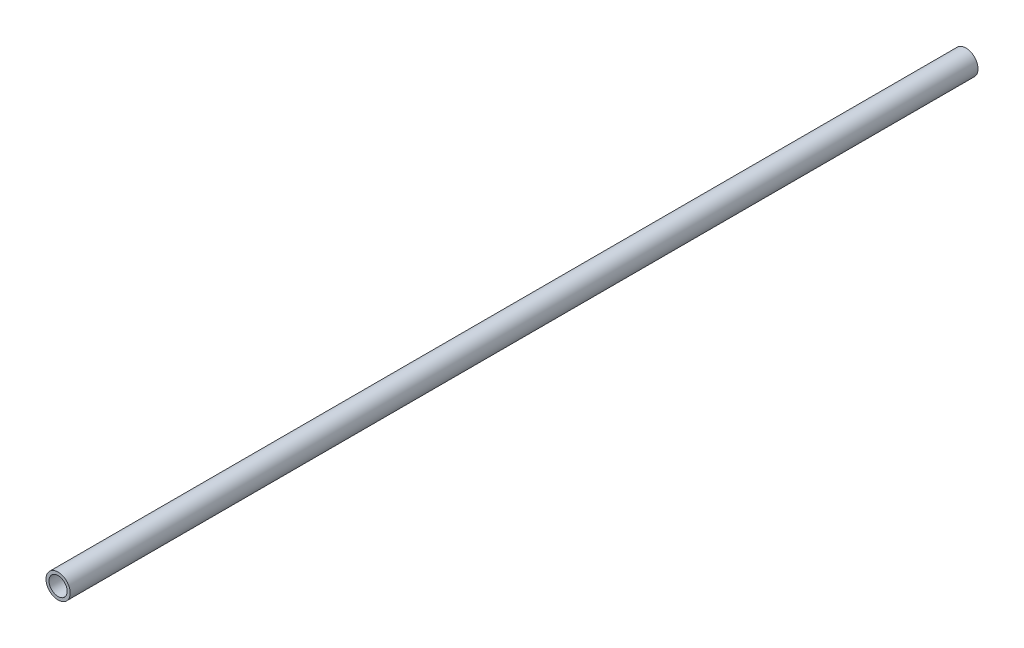
SolidWorks part; units mm, degrees
ref_plane "前视基准面" through (0, 0, 0) normal (0, 0, 1) x (1, 0, 0)
ref_plane "上视基准面" through (0, 0, 0) normal (0, 1, 0) x (1, 0, 0)
ref_plane "右视基准面" through (0, 0, 0) normal (1, 0, 0) x (0, 0, -1)
other "Configuration Table"
sketch "草图1" plane through (0, 0, 0) normal (0, 0, 1) x (1, 0, 0)
  circle A0 centre (0, 0) radius 4
  dimension "D1" = 8
extrude "拉伸-薄壁1" add sketch "草图1" along normal blind 300 thin thin type one direction reverse wall 1
